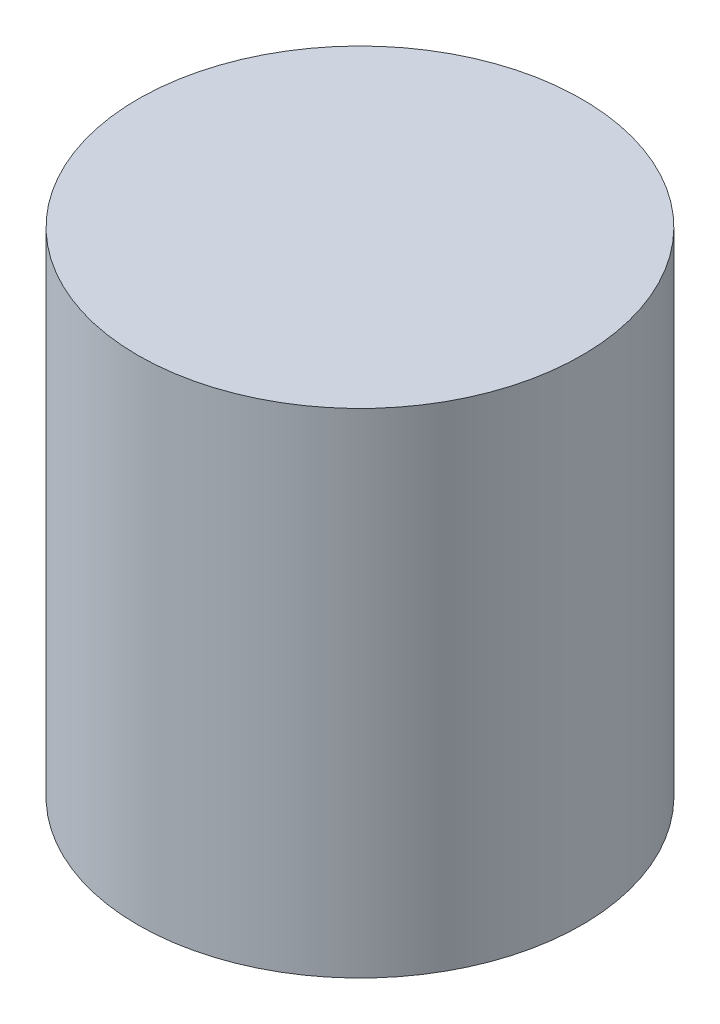
SolidWorks part; units mm, degrees
ref_plane "Front Plane" through (0, 0, 0) normal (0, 0, 1) x (1, 0, 0)
ref_plane "Top Plane" through (0, 0, 0) normal (0, 1, 0) x (1, 0, 0)
ref_plane "Right Plane" through (0, 0, 0) normal (1, 0, 0) x (0, 0, -1)
sketch "Sketch1" plane through (0, 0, 0) normal (0, 1, 0) x (1, 0, 0)
  circle A0 centre (0, 0) radius 90
  dimension "D1" = 180
extrude "Boss-Extrude1" add sketch "Sketch1" along normal blind 200
